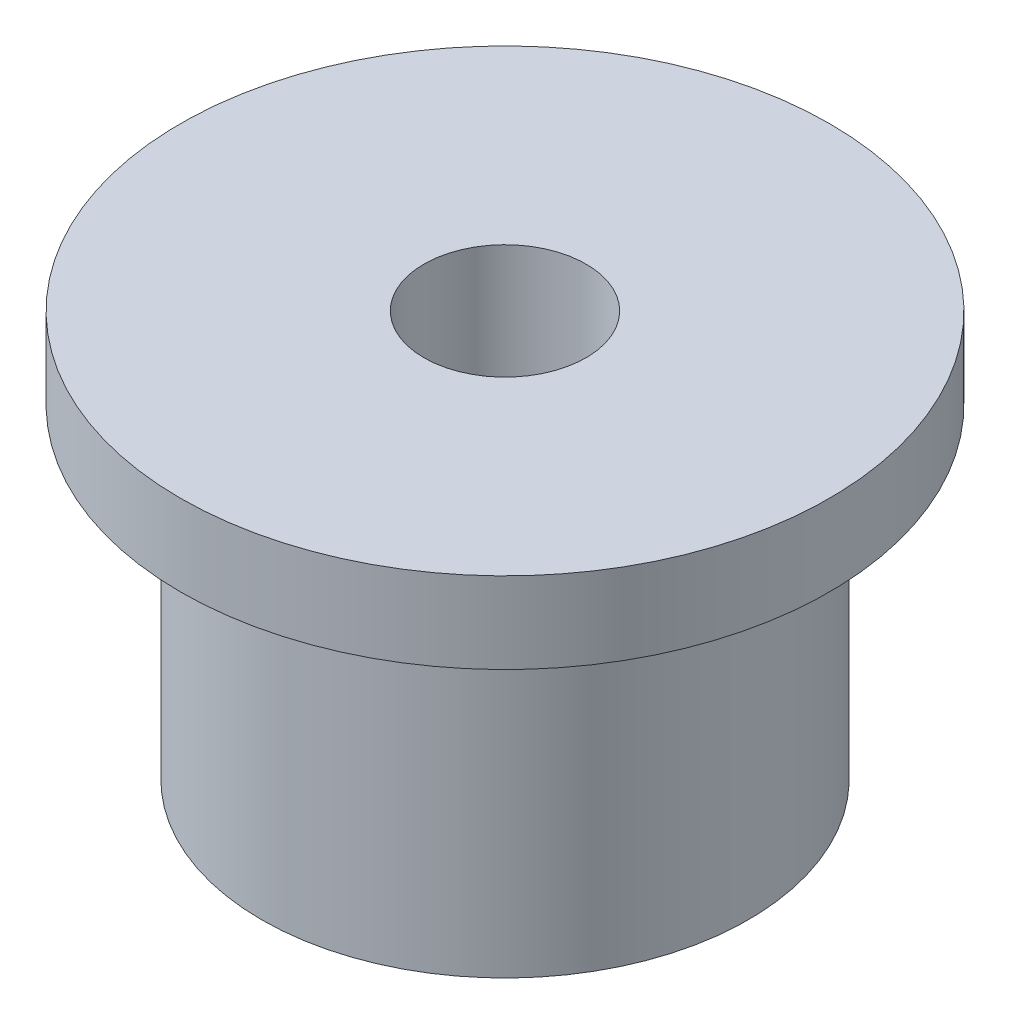
SolidWorks part; units mm, degrees
ref_plane "Front Plane" through (0, 0, 0) normal (0, 0, 1) x (1, 0, 0)
ref_plane "Top Plane" through (0, 0, 0) normal (0, 1, 0) x (1, 0, 0)
ref_plane "Right Plane" through (0, 0, 0) normal (1, 0, 0) x (0, 0, -1)
sketch "Sketch2" plane through (0, 0, 0) normal (0, 1, 0) x (1, 0, 0)
  circle A0 centre (0.8386, 0) radius 6.35
  circle A1 centre (0.8386, 0) radius 19.05
  dimension "D1" = 38.1
  dimension "D2" = 12.7
extrude "Boss-Extrude1" add sketch "Sketch2" along normal blind 25.4
sketch "Sketch3" plane through (0, 25.4, 0) normal (0, 1, 0) x (1, 0, 0)
  circle A0 centre (0.8386, 0) radius 6.35
  circle A1 centre (0.8386, 0) radius 25.4
  dimension "D1" = 50.8
extrude "Boss-Extrude3" add sketch "Sketch3" along normal blind 6.35
